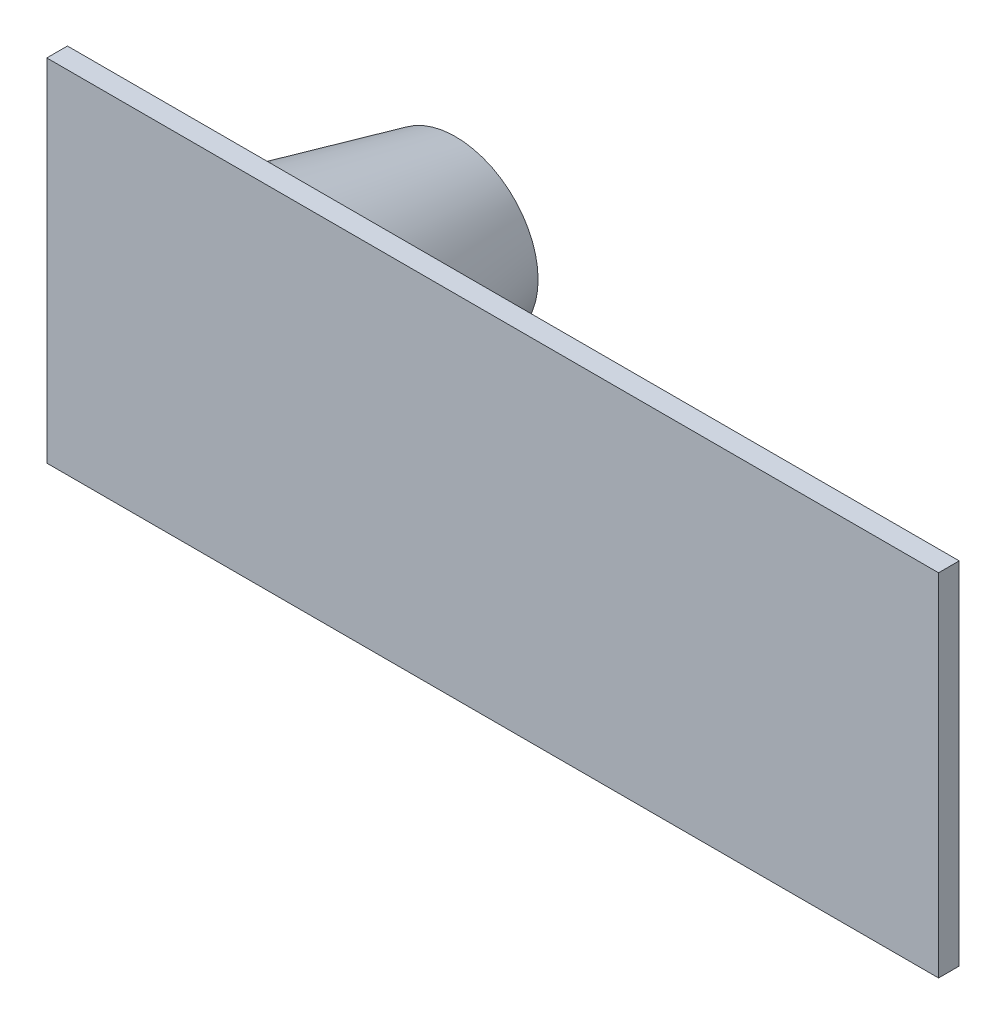
SolidWorks part; units mm, degrees
ref_plane "Front Plane" through (0, 0, 0) normal (0, 0, 1) x (1, 0, 0)
ref_plane "Top Plane" through (0, 0, 0) normal (0, 1, 0) x (1, 0, 0)
ref_plane "Right Plane" through (0, 0, 0) normal (1, 0, 0) x (0, 0, -1)
ref_plane "Plate Base y1.95" through (0, 1.95, 0) normal (0, 1, 0) x (1, 0, 0)
sketch "Series Plate 21.6 x 8.5 x 0.5 Sketch" plane through (0, 1.95, 0) normal (0, 1, 0) x (1, 0, 0)
  line L0 (9.2, 14.65) -> (30.8, 14.65)
  line L1 (30.8, 14.65) -> (30.8, 15.15)
  line L2 (30.8, 15.15) -> (9.2, 15.15)
  line L3 (9.2, 15.15) -> (9.2, 14.65)
extrude "Series Plate 21.6 x 8.5 x 0.5" add sketch "Series Plate 21.6 x 8.5 x 0.5 Sketch" along normal blind 8.5
ref_plane "Contact Axis Plane y6.95" through (0, 6.95, 0) normal (0, 1, 0) x (1, 0, 0)
sketch "Spring (compressed 4.3) Sketch" plane through (0, 6.95, 0) normal (0, 1, 0) x (1, 0, 0)
  line L0 (14.3, 14.15) -> (14.3, 20.45) construction
  line L1 (16.8, 15.15) -> (17.3, 15.15)
  line L2 (17.3, 15.15) -> (16.3, 19.45)
  line L3 (16.3, 19.45) -> (15.8, 19.45)
  line L4 (15.8, 19.45) -> (16.8, 15.15)
revolve "Spring (compressed 4.3)" add sketch "Spring (compressed 4.3) Sketch" angle 360 about L0
sketch "Dimple 0.9 Sketch" plane through (0, 6.95, 0) normal (0, 1, 0) x (1, 0, 0)
  line L0 (25.7, 14.15) -> (25.7, 17.05) construction
  line L1 (25.7, 15.15) -> (28.2, 15.15)
  line L2 (25.7, 16.05) -> (25.7, 15.15)
  arc A0 (28.2, 15.15) -> (25.7, 16.05) centre (25.7, 12.1278) ccw
revolve "Dimple 0.9" add sketch "Dimple 0.9 Sketch" angle 360 about L0
